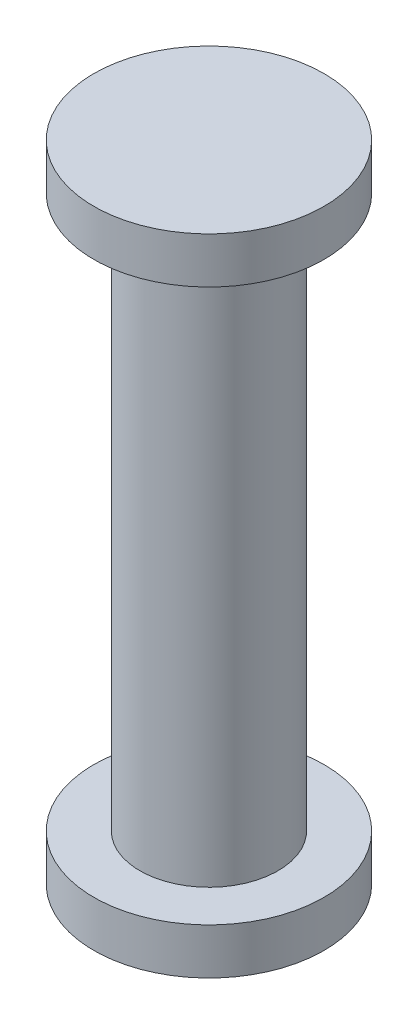
SolidWorks part; units mm, degrees
ref_plane "Front Plane" through (0, 0, 0) normal (0, 0, 1) x (1, 0, 0)
ref_plane "Top Plane" through (0, 0, 0) normal (0, 1, 0) x (1, 0, 0)
ref_plane "Right Plane" through (0, 0, 0) normal (1, 0, 0) x (0, 0, -1)
sketch "Sketch2" plane through (0, 0, 0) normal (0, 0, 1) x (1, 0, 0)
  line L0 (6.2833, -4.3897) -> (6.2833, 9.6103)
  line L1 (6.2833, 9.6103) -> (3.7833, 9.6103)
  line L2 (3.7833, 9.6103) -> (3.7833, 8.6103)
  line L3 (3.7833, 8.6103) -> (4.7833, 8.6103)
  line L4 (4.7833, 8.6103) -> (4.7833, -3.3897)
  line L5 (4.7833, -3.3897) -> (3.7833, -3.3897)
  line L6 (3.7833, -3.3897) -> (3.7833, -4.3897)
  line L7 (3.7833, -4.3897) -> (6.2833, -4.3897)
  dimension "D1" = 14
  dimension "D2" = 2.5
  dimension "D3" = 1.5
  dimension "D4" = 1
revolve "Revolve1" add sketch "Sketch2" angle 360 about L0
